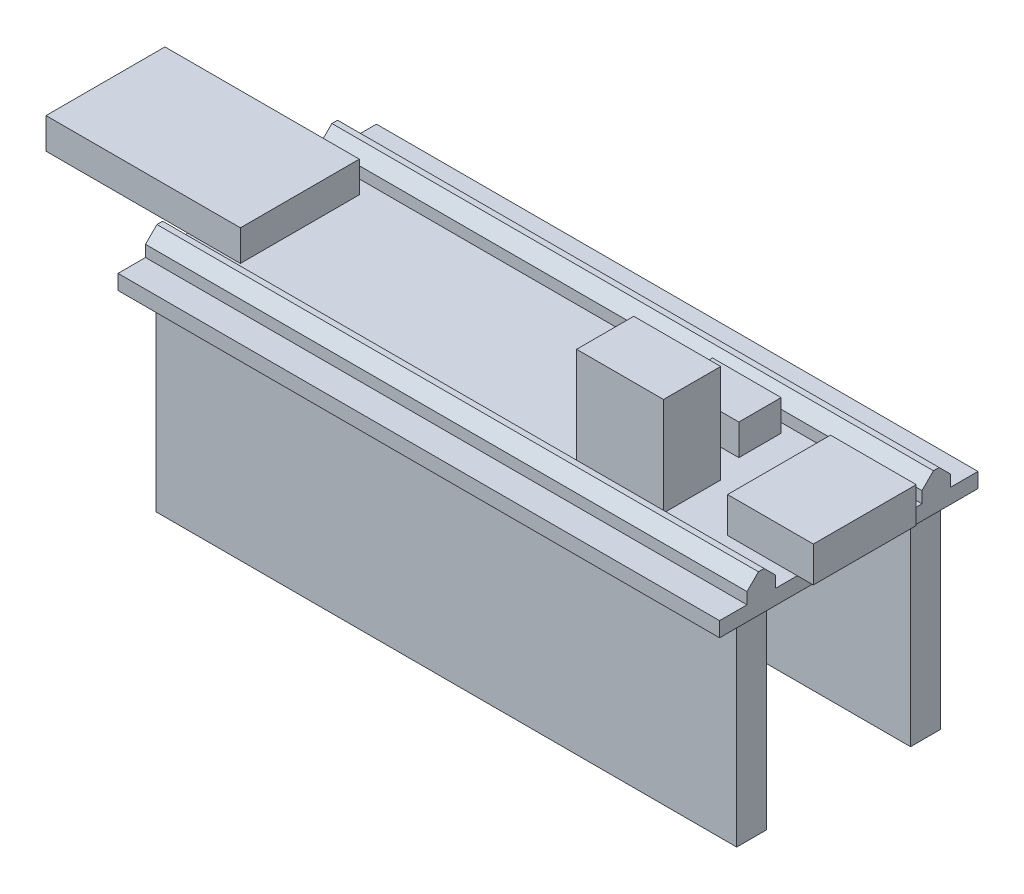
SolidWorks part; units mm, degrees
ref_plane "前视基准面" through (0, 0, 0) normal (0, 0, 1) x (1, 0, 0)
ref_plane "上视基准面" through (0, 0, 0) normal (0, 1, 0) x (1, 0, 0)
ref_plane "右视基准面" through (0, 0, 0) normal (1, 0, 0) x (0, 0, -1)
sketch "草图2" plane through (0, 0, 0) normal (0, 1, 0) x (1, 0, 0)
  line L1 (-26.3, 11.3) -> (26.3, 11.3)
  line L2 (-26.3, 11.3) -> (-26.3, -11.3)
  line L3 (-26.3, -11.3) -> (26.3, -11.3)
  line L4 (26.3, 11.3) -> (26.3, -11.3)
  line L5 (-26.3, 11.3) -> (26.3, -11.3) construction
  line L6 (-26.3, -11.3) -> (26.3, 11.3) construction
  point P0 (0, 0)
  dimension "D1" = 52.6
  dimension "D2" = 22.6
extrude "凸台-拉伸1" add sketch "草图2" along normal blind 1.3
sketch "草图3" plane through (0, 1.3, 0) normal (0, 1, 0) x (1, 0, 0)
  line L1 (-26.3, 8.9) -> (26.3, 8.9)
  line L2 (-26.3, 8.9) -> (-26.3, 6.4)
  line L3 (-26.3, 6.4) -> (26.3, 6.4)
  line L4 (26.3, -11.3) -> (26.3, 11.3)
  line L5 (26.3, 11.3) -> (-26.3, 11.3)
  line L6 (-26.3, 11.3) -> (-26.3, -11.3)
  line L7 (-26.3, -11.3) -> (26.3, -11.3)
  line L8 (26.3, -11.3) -> (26.3, 11.3)
  line L9 (26.3, 11.3) -> (-26.3, 11.3)
  line L10 (-26.3, 11.3) -> (-26.3, -11.3)
  line L11 (-26.3, -11.3) -> (26.3, -11.3)
  line L12 (26.3, 8.9) -> (26.3, 6.4)
  line L13 (-26.3, -6.4) -> (26.3, -6.4)
  line L14 (-26.3, -6.4) -> (-26.3, -8.9)
  line L15 (-26.3, -8.9) -> (26.3, -8.9)
  line L16 (26.3, -6.4) -> (26.3, -8.9)
  line M9 (26.3, -11.3) -> (26.3, 11.3)
  line M11 (-26.3, 11.3) -> (-26.3, -11.3)
  dimension "D2" = 2.4
  dimension "D3" = 2.4
  dimension "D4" = 2.5
  dimension "D5" = 2.5
  dimension "D1" = 0
extrude "凸台-拉伸2" add sketch "草图3" along normal blind 2 contours L3 L1 M11 M9 | L10 L15 L8 L13
chamfer "倒角1" distance 1 angle 45 4 edges at (0, 3.3, 8.9) (0, 3.3, 6.4) (0, 3.3, -6.4) (0, 3.3, -8.9)
sketch "草图4" plane through (0, 1.3, 0) normal (0, 1, 0) x (1, 0, 0)
  line L0 (0, 0) -> (26.3, 0) construction
  line L1 (0, 0) -> (-26.3, 0) construction
  line L3 (20.2, 4.5) -> (27.7, 4.5)
  line L4 (-26.3, -6.4) -> (26.3, -6.4)
  line L5 (26.3, -6.4) -> (26.3, 6.4)
  line L6 (26.3, 6.4) -> (-26.3, 6.4)
  line L7 (-26.3, 6.4) -> (-26.3, -6.4)
  line L8 (-26.3, -6.4) -> (26.3, -6.4)
  line L9 (26.3, -6.4) -> (26.3, 6.4)
  line L10 (26.3, 6.4) -> (-26.3, 6.4)
  line L11 (-26.3, 6.4) -> (-26.3, -6.4)
  line L12 (20.2, 4.5) -> (20.2, -4.5)
  line L13 (20.2, -4.5) -> (27.7, -4.5)
  line L14 (27.7, 4.5) -> (27.7, -4.5)
  line L15 (20.2, 4.5) -> (27.7, -4.5) construction
  line L16 (20.2, -4.5) -> (27.7, 4.5) construction
  point P6 (23.95, 0)
  dimension "D2" = 9
  dimension "D3" = 7.5
  dimension "D4" = 1.4
  dimension "D1" = 0
extrude "凸台-拉伸3" add sketch "草图4" along normal blind 3.1 contours L12 L13 L9 L3 | L14 L3 L9 L13
sketch "草图5" plane through (0, 1.3, 0) normal (0, 1, 0) x (1, 0, 0)
  line L0 (0, 0) -> (-26.3, 0) construction
  line L2 (-38.7, 5.2) -> (-21.7, 5.2)
  line L3 (-38.7, 5.2) -> (-38.7, -5.2)
  line L4 (-38.7, -5.2) -> (-21.7, -5.2)
  line L5 (-21.7, 5.2) -> (-21.7, -5.2)
  line L6 (-38.7, 5.2) -> (-21.7, -5.2) construction
  line L7 (-38.7, -5.2) -> (-21.7, 5.2) construction
  line L8 (26.3, -6.4) -> (26.3, -4.5)
  line L9 (26.3, -4.5) -> (20.2, -4.5)
  line L10 (20.2, -4.5) -> (20.2, 4.5)
  line L11 (20.2, 4.5) -> (26.3, 4.5)
  line L12 (26.3, 4.5) -> (26.3, 6.4)
  line L13 (26.3, 6.4) -> (-26.3, 6.4)
  line L14 (-26.3, 6.4) -> (-26.3, -6.4)
  line L15 (-26.3, -6.4) -> (26.3, -6.4)
  line L16 (26.3, -6.4) -> (26.3, -4.5)
  line L17 (26.3, -4.5) -> (20.2, -4.5)
  line L18 (20.2, -4.5) -> (20.2, 4.5)
  line L19 (20.2, 4.5) -> (26.3, 4.5)
  line L20 (26.3, 4.5) -> (26.3, 6.4)
  line L21 (26.3, 6.4) -> (-26.3, 6.4)
  line L22 (-26.3, 6.4) -> (-26.3, -6.4)
  line L23 (-26.3, -6.4) -> (26.3, -6.4)
  point P6 (-30.2, 0)
  line M19 (-26.3, 6.4) -> (-26.3, -6.4)
  dimension "D2" = 10.4
  dimension "D3" = 17
  dimension "D4" = 4.6
  dimension "D1" = 0
extrude "凸台-拉伸4" add sketch "草图5" along normal blind 2.7 contours L3 L4 L2 M19 | L5 L2 L4 M19
sketch "草图6" plane through (0, 1.3, 0) normal (0, 1, 0) x (1, 0, 0)
  line L0 (-26.3, -11.3) -> (26.3, -11.3) construction
  line L1 (8.1, -0.6) -> (15.7, -0.6)
  line L2 (8.1, -0.6) -> (8.1, -5.6)
  line L3 (8.1, -5.6) -> (15.7, -5.6)
  line L4 (15.7, -0.6) -> (15.7, -5.6)
  line L12 (-21.7, 5.2) -> (-21.7, -5.2)
  line L13 (-21.7, -5.2) -> (-26.3, -5.2)
  line L14 (-26.3, -5.2) -> (-26.3, -6.4)
  line L15 (-26.3, -6.4) -> (26.3, -6.4)
  line L16 (26.3, -6.4) -> (26.3, -4.5)
  line L17 (26.3, -4.5) -> (20.2, -4.5)
  line L18 (20.2, -4.5) -> (20.2, 4.5)
  line L19 (20.2, 4.5) -> (26.3, 4.5)
  line L20 (26.3, 4.5) -> (26.3, 6.4)
  line L21 (26.3, 6.4) -> (-26.3, 6.4)
  line L22 (-26.3, 6.4) -> (-26.3, 5.2)
  line L23 (-26.3, 5.2) -> (-21.7, 5.2)
  line L24 (-21.7, 5.2) -> (-21.7, -5.2)
  line L25 (-21.7, -5.2) -> (-26.3, -5.2)
  line L26 (-26.3, -5.2) -> (-26.3, -6.4)
  line L27 (-26.3, -6.4) -> (26.3, -6.4)
  line L28 (26.3, -6.4) -> (26.3, -4.5)
  line L29 (26.3, -4.5) -> (20.2, -4.5)
  line L30 (20.2, -4.5) -> (20.2, 4.5)
  line L31 (20.2, 4.5) -> (26.3, 4.5)
  line L32 (26.3, 4.5) -> (26.3, 6.4)
  line L33 (26.3, 6.4) -> (-26.3, 6.4)
  line L34 (-26.3, 6.4) -> (-26.3, 5.2)
  line L35 (-26.3, 5.2) -> (-21.7, 5.2)
  dimension "D2" = 10.7
  dimension "D3" = 5
  dimension "D4" = 7.6
  dimension "D5" = 18.2
  dimension "D1" = 0
extrude "凸台-拉伸5" add sketch "草图6" along normal blind 8.6 contours L2 L1 L4 L3
sketch "草图7" plane through (0, 1.3, 0) normal (0, 1, 0) x (1, 0, 0)
  line L0 (26.3, 4.5) -> (26.3, 6.4) construction
  line L1 (8.8, 5.586) -> (14.8, 5.586)
  line L2 (8.8, 5.586) -> (8.8, 1.886)
  line L3 (8.8, 1.886) -> (14.8, 1.886)
  line L4 (14.8, 5.586) -> (14.8, 1.886)
  dimension "D1" = 3.7
  dimension "D2" = 6
  dimension "D3" = 17.5
extrude "凸台-拉伸6" add sketch "草图7" along normal blind 2.7
sketch "草图8" plane through (0, 0, 0) normal (0, -1, 0) x (1, 0, 0)
  line L0 (0, 0) -> (26.3, 0) construction
  line L1 (26.3, 11.3) -> (26.3, -11.3) construction
  line L11 (-25.4, -6.3) -> (25.4, -6.3)
  line L12 (-25.4, 8.9) -> (25.4, 8.9)
  line L13 (-25.4, 8.9) -> (-25.4, 6.3)
  line L14 (-25.4, 6.3) -> (25.4, 6.3)
  line L15 (25.4, 8.9) -> (25.4, 6.3)
  line L16 (25.4, -8.9) -> (25.4, -6.3)
  line L17 (-25.4, -8.9) -> (25.4, -8.9)
  line L18 (-25.4, -8.9) -> (-25.4, -6.3)
  dimension "D1" = 2.6
  dimension "D2" = 17.8
  dimension "D3" = 50.8
  dimension "D4" = 25.4
extrude "凸台-拉伸8" add sketch "草图8" along normal blind 17.5
